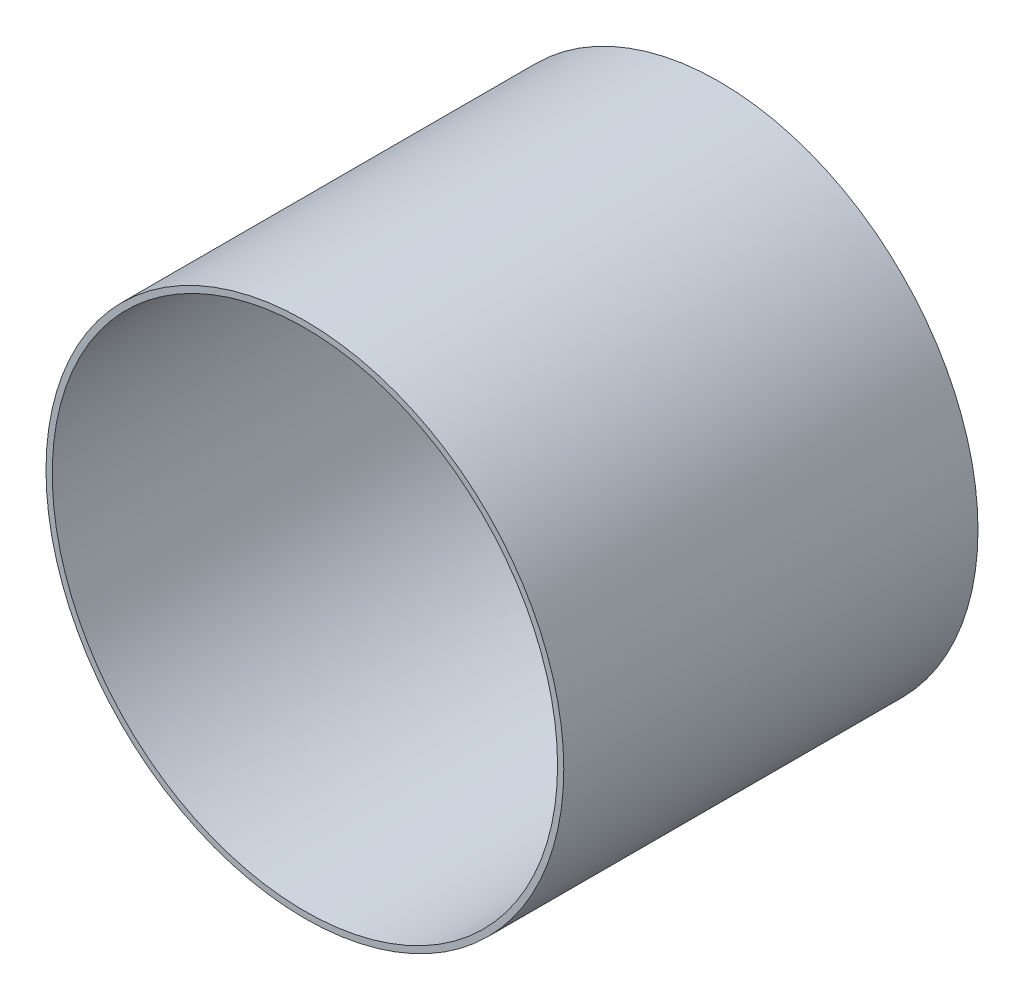
SolidWorks part; units mm, degrees
ref_plane "Alzado" through (0, 0, 0) normal (0, 0, 1) x (1, 0, 0)
ref_plane "Planta" through (0, 0, 0) normal (0, 1, 0) x (1, 0, 0)
ref_plane "Vista lateral" through (0, 0, 0) normal (1, 0, 0) x (0, 0, -1)
sketch "Croquis1" plane through (0, 0, 0) normal (0, 0, 1) x (1, 0, 0)
  circle A0 centre (-50.6624, 7.1115) radius 25
  circle A1 centre (-50.6624, 7.1115) radius 24.4
  dimension "D1" = 48.8
  dimension "D2" = 50
extrude "Saliente-Extruir1" add sketch "Croquis1" along normal blind 40
